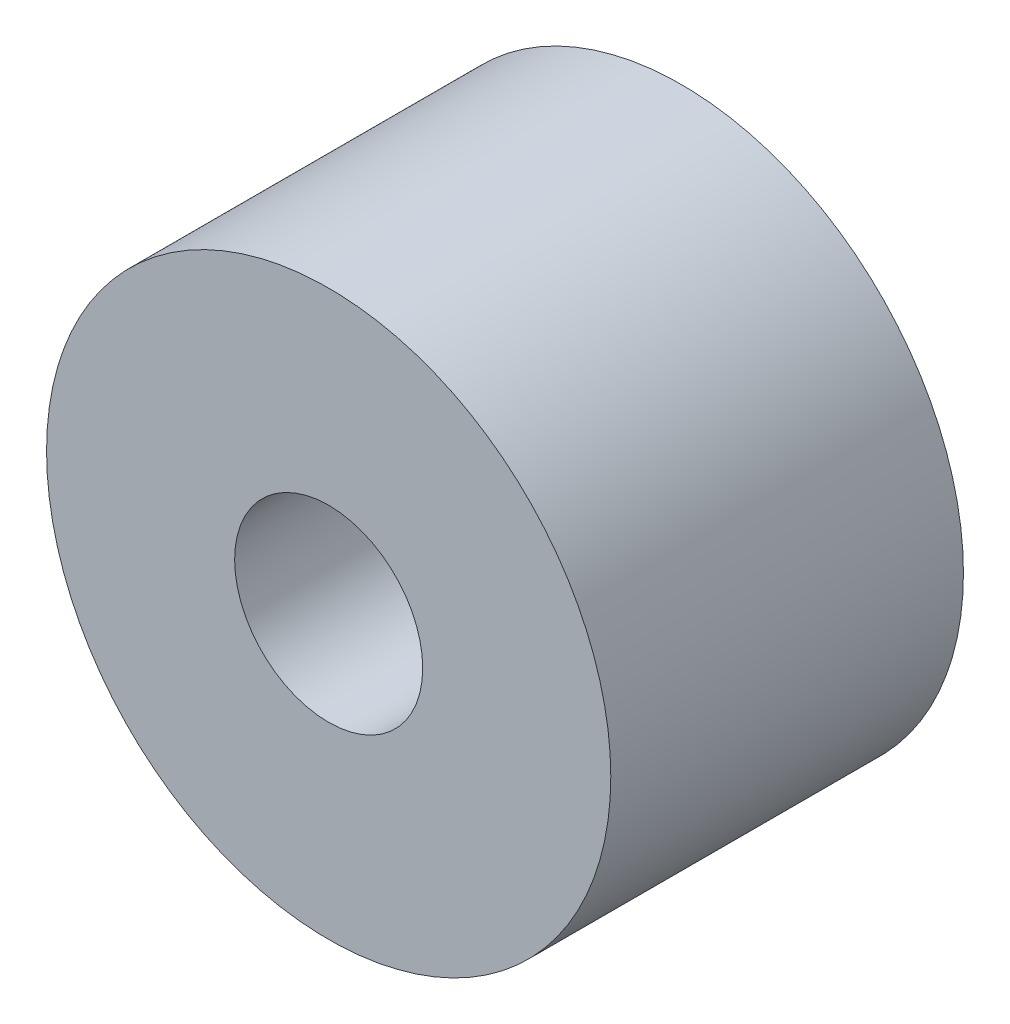
SolidWorks part; units mm, degrees
ref_plane "前视基准面" through (0, 0, 0) normal (0, 0, 1) x (1, 0, 0)
ref_plane "上视基准面" through (0, 0, 0) normal (0, 1, 0) x (1, 0, 0)
ref_plane "右视基准面" through (0, 0, 0) normal (1, 0, 0) x (0, 0, -1)
other "Configuration Table"
sketch "草图1" plane through (0, 0, 0) normal (0, 0, 1) x (1, 0, 0)
  circle A0 centre (0, 0) radius 12
extrude "凸台-拉伸1" add sketch "草图1" along normal blind 15
sketch "草图2" plane through (0, 0, 0) normal (0, 0, 1) x (1, 0, 0)
  circle A0 centre (0, 0) radius 4
extrude "切除-拉伸1" cut sketch "草图2" along normal blind 15
